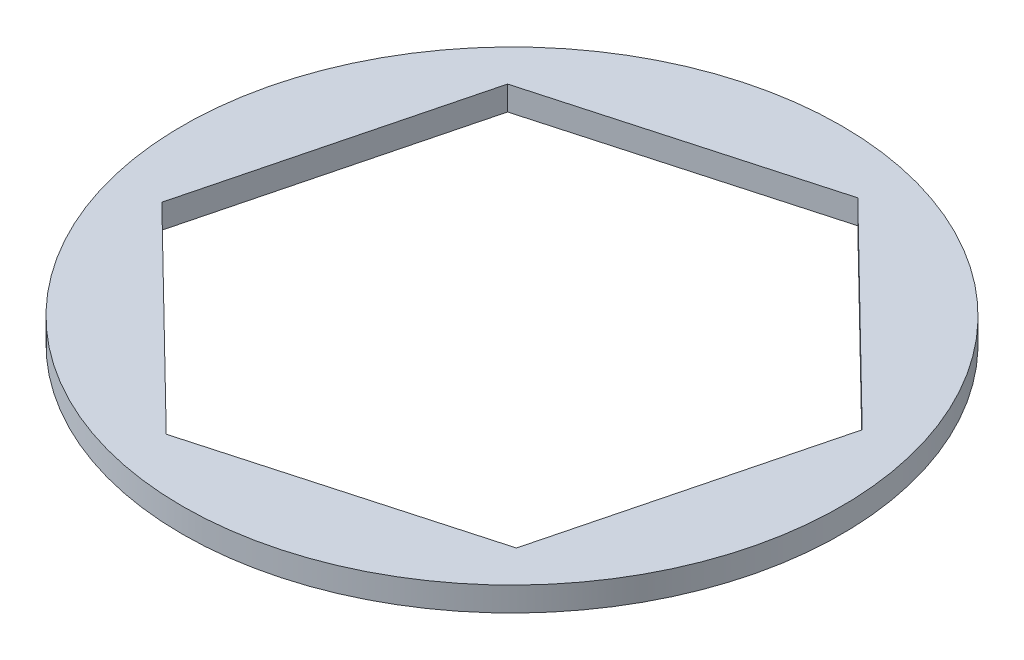
SolidWorks part; units mm, degrees
ref_plane "Front Plane" through (0, 0, 0) normal (0, 0, 1) x (1, 0, 0)
ref_plane "Top Plane" through (0, 0, 0) normal (0, 1, 0) x (1, 0, 0)
ref_plane "Right Plane" through (0, 0, 0) normal (1, 0, 0) x (0, 0, -1)
sketch "Sketch1" plane through (0, 0, 0) normal (0, 1, 0) x (1, 0, 0)
  line L1 (2.0381, 7.9553) -> (-5.8704, 5.7427)
  line L2 (-5.8704, 5.7427) -> (-7.9086, -2.2126)
  line L3 (-7.9086, -2.2126) -> (-2.0381, -7.9553)
  line L4 (-2.0381, -7.9553) -> (5.8704, -5.7427)
  line L5 (5.8704, -5.7427) -> (7.9086, 2.2126)
  line L6 (7.9086, 2.2126) -> (2.0381, 7.9553)
  circle A0 centre (0, 0) radius 9.525
  circle A1 centre (0, 0) radius 7.112 construction
  dimension "D1" = 19.05
  dimension "D2" = 14.224
extrude "Boss-Extrude1" add sketch "Sketch1" along normal blind 0.7
